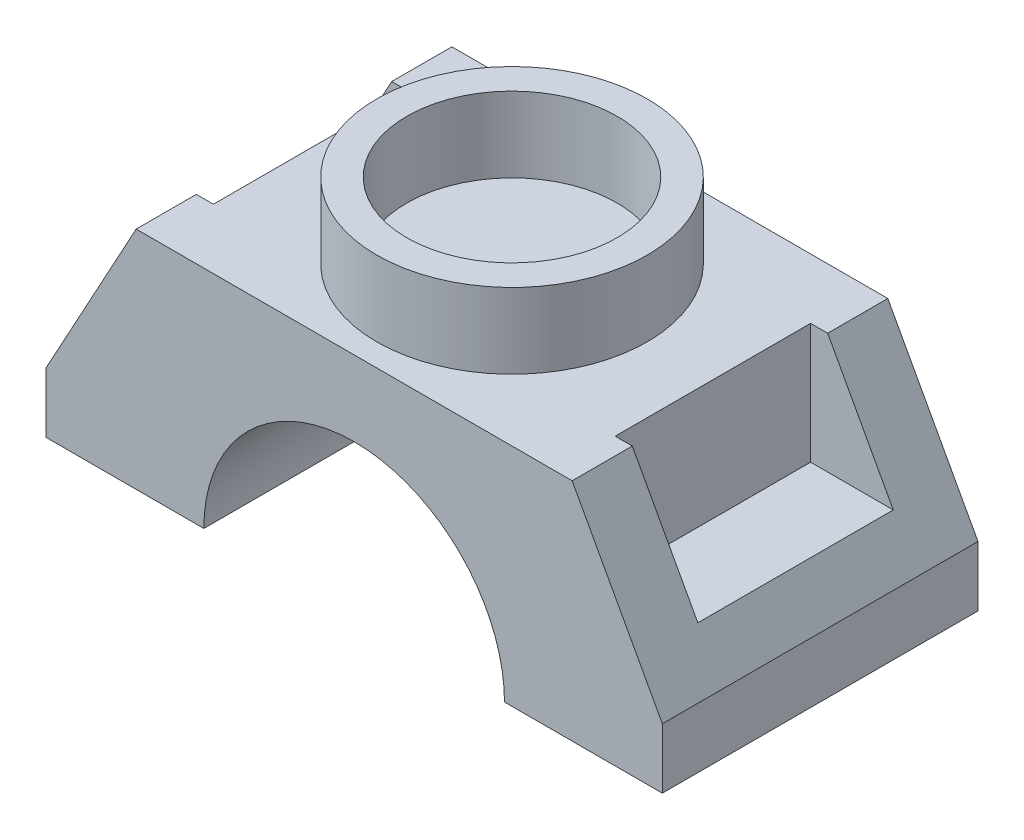
SolidWorks part; units mm, degrees
ref_plane "Front Plane" through (0, 0, 0) normal (0, 0, 1) x (1, 0, 0)
ref_plane "Top Plane" through (0, 0, 0) normal (0, 1, 0) x (1, 0, 0)
ref_plane "Right Plane" through (0, 0, 0) normal (1, 0, 0) x (0, 0, -1)
sketch "Sketch1" plane through (0, 0, 0) normal (0, 0, 1) x (1, 0, 0)
  line L0 (-30.8179, 0) -> (-30.8179, 8)
  line L2 (-18.8179, 30) -> (39.1821, 30)
  line L4 (51.1821, 8) -> (51.1821, 0)
  line L5 (-30.8179, 0) -> (-9.8179, 0)
  line L6 (30.1821, 0) -> (51.1821, 0)
  line L7 (-30.8179, 8) -> (-18.8179, 30)
  line L8 (39.1821, 30) -> (51.1821, 8)
  arc A0 (-9.8179, 0) -> (30.1821, 0) centre (10.1821, 0) cw
  dimension "D4" = 20
  dimension "D1" = 82
  dimension "D2" = 58
  dimension "D3" = 8
  dimension "D5" = 30
extrude "Boss-Extrude1" add sketch "Sketch1" against normal blind 42
sketch "Sketch2" plane through (0, 30, 0) normal (0, 1, 0) x (1, 0, 0)
  circle A1 centre (10.1821, 21) radius 18
  circle A2 centre (10.1821, 21) radius 14
extrude "Boss-Extrude2" add sketch "Sketch2" along normal blind 10
ref_plane "Plane1" through (0, 0, -8) normal (0, 0, 1) x (1, 0, 0)
sketch "Sketch3" plane through (0, 0, -8) normal (0, 0, 1) x (1, 0, 0)
  line L4 (36.9093, 30) -> (36.9093, 14)
  line L5 (39.1821, 30) -> (-18.8179, 30) construction
  line L6 (36.9093, 14) -> (47.9093, 14)
  line L7 (51.1821, 8) -> (39.1821, 30) construction
  line L8 (47.9093, 14) -> (39.1821, 30)
  line L9 (39.1821, 30) -> (36.9093, 30)
  line L10 (-16.5452, 30) -> (-16.5452, 14)
  line L11 (-16.5452, 14) -> (-27.5452, 14)
  line L12 (-18.8179, 30) -> (-30.8179, 8) construction
  line L13 (-27.5452, 14) -> (-18.8179, 30)
  line L14 (-18.8179, 30) -> (-16.5452, 30)
  dimension "D1" = 16
  dimension "D2" = 11
extrude "Cut-Extrude1" cut sketch "Sketch3" against normal blind 26
